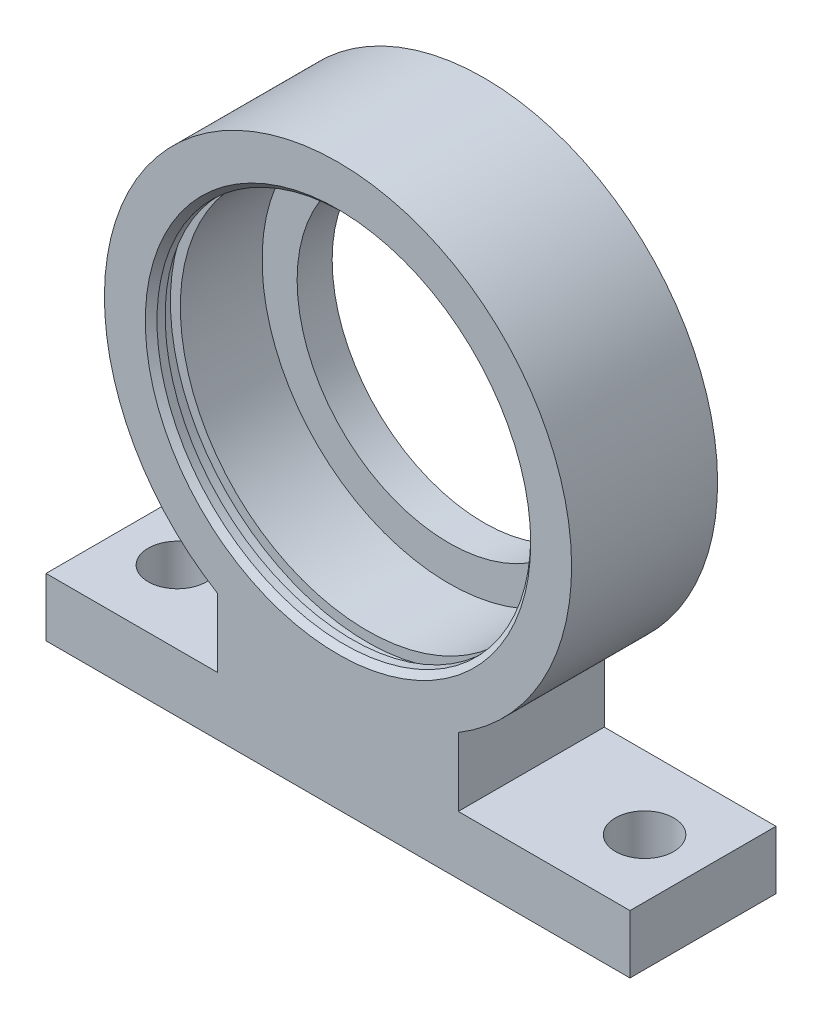
SolidWorks part; units mm, degrees
material "7075-T6 (SN)"
ref_plane "Front Plane" through (0, 0, 0) normal (0, 0, 1) x (1, 0, 0)
ref_plane "Top Plane" through (0, 0, 0) normal (0, 1, 0) x (1, 0, 0)
ref_plane "Right Plane" through (0, 0, 0) normal (1, 0, 0) x (0, 0, -1)
sketch "Sketch1" plane through (0, 0, 0) normal (0, 0, 1) x (1, 0, 0)
  line L0 (0, 0) -> (0, -28) construction
  line L1 (25, -28) -> (-25, -28)
  line L2 (-25, -28) -> (-25, -23)
  line L3 (-25, -23) -> (-10.2978, -23)
  line L4 (-10.2978, -23) -> (-10.2978, -17.1451)
  line L5 (25, -28) -> (25, -23)
  line L6 (25, -23) -> (10.2978, -23)
  line L7 (10.2978, -23) -> (10.2978, -17.1451)
  circle A0 centre (0, 0) radius 10 construction
  arc A1 (10.2978, -17.1451) -> (-10.2978, -17.1451) centre (0, 0) ccw
  circle A2 centre (0, 0) radius 13
  dimension "D1" = 20
  dimension "D2" = 40
  dimension "D6" = 7
  dimension "D3" = 28
  dimension "D4" = 50
  dimension "D5" = 5
extrude "Boss-Extrude1" add sketch "Sketch1" along normal blind 12.5
sketch "Sketch2" plane through (0, 0, 0) normal (0, 0, 1) x (1, 0, 0)
  circle A0 centre (0, 0) radius 16
  dimension "D1" = 32
extrude "Cut-Extrude1" cut sketch "Sketch2" along normal through all from offset 3
sketch "Sketch3" plane through (0, -23, 0) normal (0, 1, 0) x (1, 0, 0)
  line L0 (-25, -12.5) -> (-25, 0) construction
  line L4 (-20, -6.25) -> (-20, 0) construction
  line L5 (-10.2978, 0) -> (-25, 0) construction
  line L6 (-20, -6.25) -> (-20, -12.5) construction
  line L7 (-10.2978, -12.5) -> (-25, -12.5) construction
  line L8 (0, 0) -> (0, -15.9497) construction
  line L9 (20, 0) -> (-20, 0) construction
  circle A0 centre (-20, -6.25) radius 2.5
  circle A1 centre (20, -6.25) radius 2.5
  dimension "D2" = 5
  dimension "D1" = 5
extrude "Cut-Extrude2" cut sketch "Sketch3" against normal through all
sketch "Sketch5" plane through (0, 0, 0) normal (0, 0, 1) x (1, 0, 0)
  circle A0 centre (0, 0) radius 16.85
  circle A1 centre (0, 0) radius 16
  dimension "D1" = 32
  dimension "D2" = 33.7
extrude "Cut-Extrude3" cut sketch "Sketch5" along normal blind 1.3 from offset 10
chamfer "Chamfer2" distance 0.5 angle 45 1 edges at (16, 0, 12.5)
